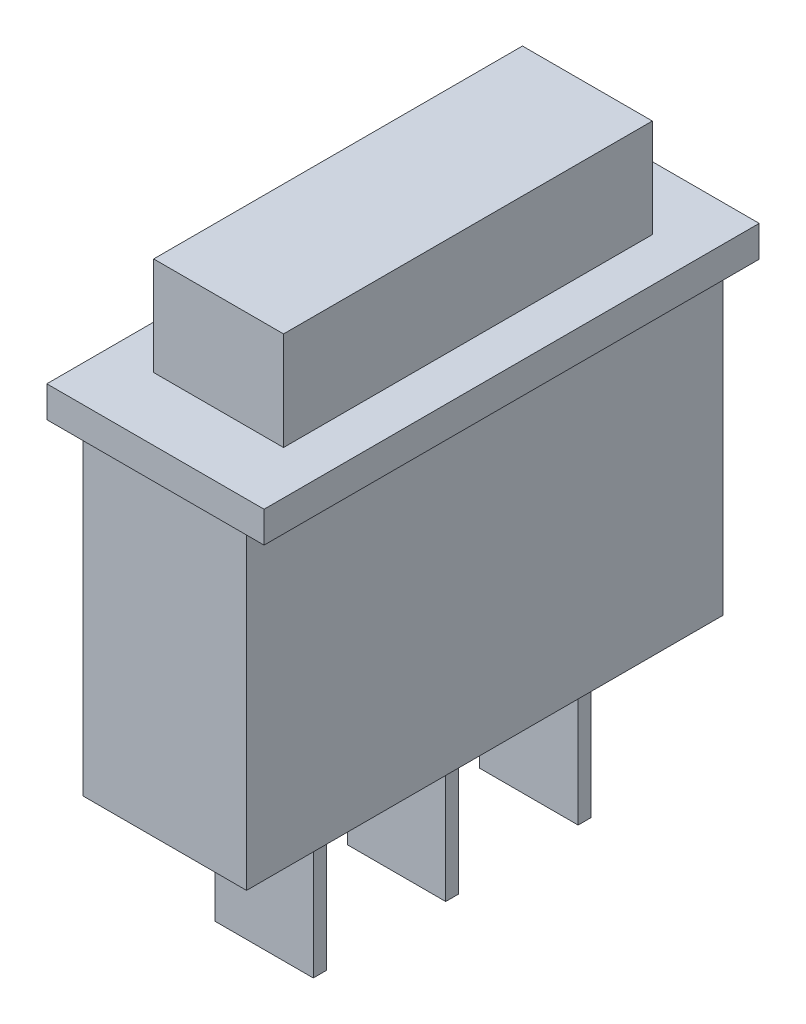
SolidWorks part; units mm, degrees
ref_plane "Front Plane" through (0, 0, 0) normal (0, 0, 1) x (1, 0, 0)
ref_plane "Top Plane" through (0, 0, 0) normal (0, 1, 0) x (1, 0, 0)
ref_plane "Right Plane" through (0, 0, 0) normal (1, 0, 0) x (0, 0, -1)
sketch "Sketch1" plane through (0, 0, 0) normal (0, 1, 0) x (1, 0, 0)
  line L1 (0, 0) -> (10.541, 0)
  line L2 (0, 0) -> (0, 30.734)
  line L3 (0, 30.734) -> (10.541, 30.734)
  line L4 (10.541, 0) -> (10.541, 30.734)
  dimension "D1" = 10.541
  dimension "D2" = 30.734
extrude "Boss-Extrude1" add sketch "Sketch1" along normal blind 20.4724
sketch "Sketch2" plane through (0, 20.4724, 0) normal (0, 1, 0) x (1, 0, 0)
  line L0 (0, 0) -> (10.541, 30.734) construction
  line L2 (12.2809, -0.6096) -> (-1.7399, -0.6096)
  line L3 (12.2809, -0.6096) -> (12.2809, 31.3436)
  line L4 (12.2809, 31.3436) -> (-1.7399, 31.3436)
  line L5 (-1.7399, -0.6096) -> (-1.7399, 31.3436)
  line L6 (12.2809, -0.6096) -> (-1.7399, 31.3436) construction
  line L7 (12.2809, 31.3436) -> (-1.7399, -0.6096) construction
  point P4 (5.2705, 15.367)
  dimension "D1" = 14.0208
  dimension "D2" = 31.9532
extrude "Boss-Extrude2" add sketch "Sketch2" along normal blind 2.0066
sketch "Sketch3" plane through (0, 22.479, 0) normal (0, 1, 0) x (1, 0, 0)
  line L0 (-1.7399, -0.6096) -> (12.2809, 31.3436) construction
  line L2 (9.4615, 3.4671) -> (1.0795, 3.4671)
  line L3 (9.4615, 3.4671) -> (9.4615, 27.2669)
  line L4 (9.4615, 27.2669) -> (1.0795, 27.2669)
  line L5 (1.0795, 3.4671) -> (1.0795, 27.2669)
  line L6 (9.4615, 3.4671) -> (1.0795, 27.2669) construction
  line L7 (9.4615, 27.2669) -> (1.0795, 3.4671) construction
  point P4 (5.2705, 15.367)
  dimension "D1" = 8.382
  dimension "D2" = 23.7998
extrude "Boss-Extrude3" add sketch "Sketch3" along normal blind 6.35
ref_plane "Plane1" through (0, 0, -15.367) normal (0, 0, -1) x (-1, 0, 0)
ref_plane "Plane2" through (5.2705, 0, 0) normal (1, 0, 0) x (0, 0, -1)
sketch "Sketch4" plane through (0, 0, 0) normal (0, -1, 0) x (1, 0, 0)
  line L0 (5.2705, -30.734) -> (5.2705, 0) construction
  line L1 (10.541, -30.734) -> (0, -30.734) construction
  line L2 (0, 0) -> (10.541, 0) construction
  line L3 (10.541, -15.367) -> (0, -15.367) construction
  line L4 (8.4455, -23.4941) -> (2.0955, -23.4941)
  line L5 (8.4455, -23.4941) -> (8.4455, -24.3323)
  line L6 (8.4455, -24.3323) -> (2.0955, -24.3323)
  line L7 (2.0955, -23.4941) -> (2.0955, -24.3323)
  line L8 (8.4455, -23.4941) -> (2.0955, -24.3323) construction
  line L9 (8.4455, -24.3323) -> (2.0955, -23.4941) construction
  line L10 (2.0955, -15.7861) -> (8.4455, -15.7861)
  line L11 (2.0955, -15.7861) -> (2.0955, -14.9479)
  line L12 (2.0955, -14.9479) -> (8.4455, -14.9479)
  line L13 (8.4455, -15.7861) -> (8.4455, -14.9479)
  line L14 (2.0955, -15.7861) -> (8.4455, -14.9479) construction
  line L15 (2.0955, -14.9479) -> (8.4455, -15.7861) construction
  line L16 (8.4455, -6.4017) -> (2.0955, -7.2399) construction
  line L17 (8.4455, -7.2399) -> (2.0955, -6.4017) construction
  line L18 (2.0955, -7.2399) -> (2.0955, -6.4017)
  line L19 (8.4455, -6.4017) -> (2.0955, -6.4017)
  line L20 (8.4455, -7.2399) -> (8.4455, -6.4017)
  line L21 (8.4455, -7.2399) -> (2.0955, -7.2399)
  line L22 (10.541, 0) -> (10.541, -30.734) construction
  line L23 (0, -30.734) -> (0, 0) construction
  point P6 (5.2705, -23.9132)
  point P11 (5.2705, -15.367)
  point P20 (5.2705, -6.8208)
  dimension "D1" = 0.8382
  dimension "D2" = 6.35
extrude "Boss-Extrude4" add sketch "Sketch4" along normal blind 9.144
